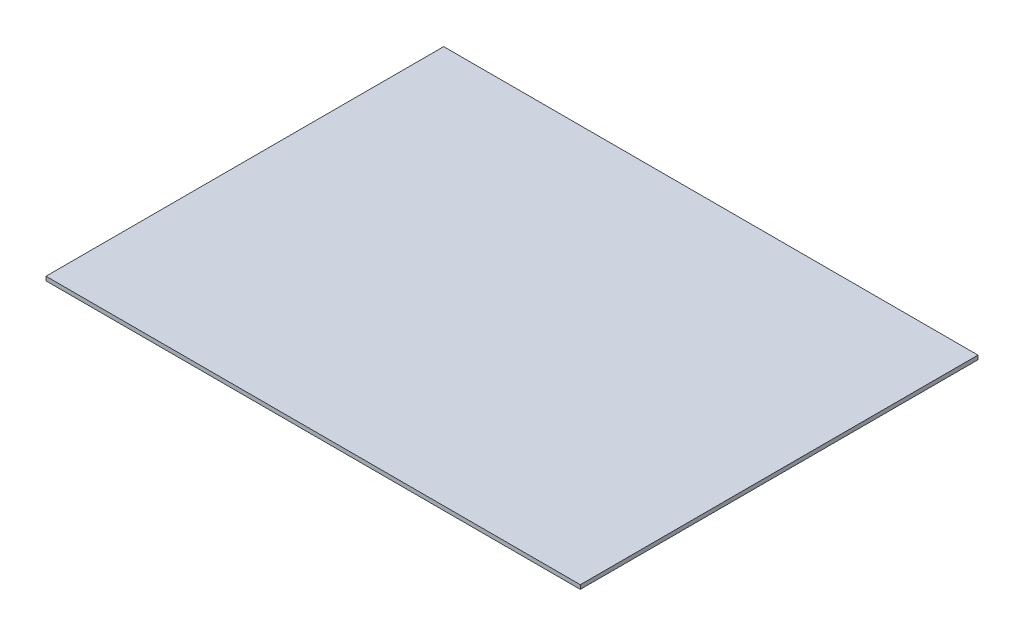
SolidWorks part; units mm, degrees
ref_plane "Front Plane" through (0, 0, 0) normal (0, 0, 1) x (1, 0, 0)
ref_plane "Top Plane" through (0, 0, 0) normal (0, 1, 0) x (1, 0, 0)
ref_plane "Right Plane" through (0, 0, 0) normal (1, 0, 0) x (0, 0, -1)
sketch "Sketch1" plane through (0, 0, 0) normal (0, 1, 0) x (1, 0, 0)
  line L1 (-197.5, 147) -> (197.5, 147)
  line L2 (-197.5, 147) -> (-197.5, -147)
  line L3 (-197.5, -147) -> (197.5, -147)
  line L4 (197.5, 147) -> (197.5, -147)
  line L5 (-197.5, 147) -> (197.5, -147) construction
  line L6 (-197.5, -147) -> (197.5, 147) construction
  point P0 (0, 0)
  dimension "D1" = 294
  dimension "D2" = 395
extrude "Boss-Extrude1" add sketch "Sketch1" along normal blind 3
